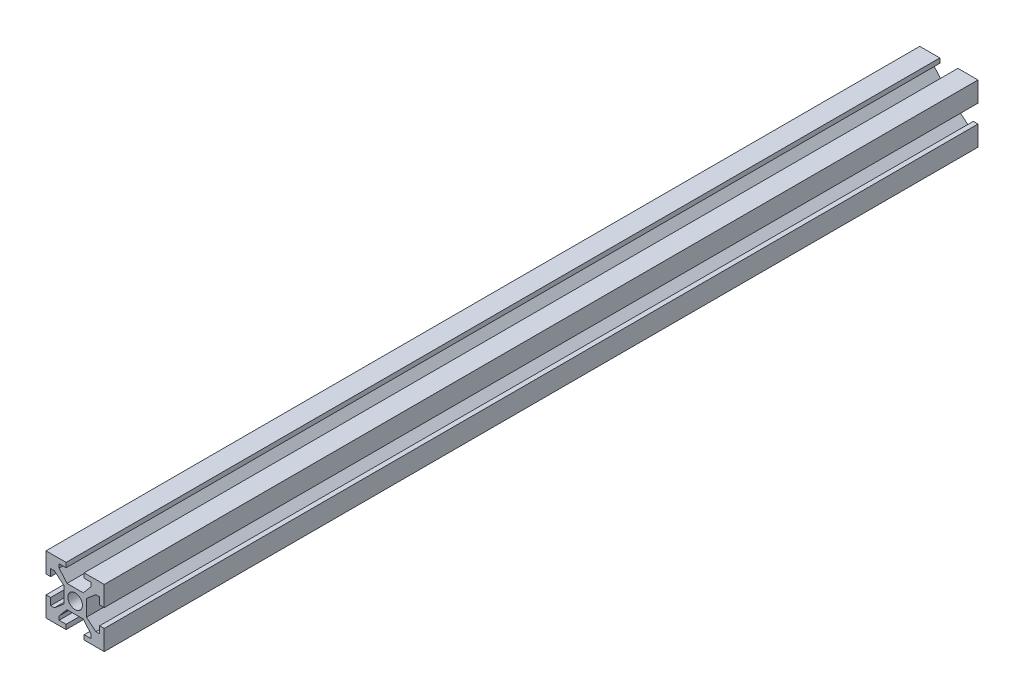
SolidWorks part; units mm, degrees
ref_plane "前视基准面" through (0, 0, 0) normal (0, 0, 1) x (1, 0, 0)
ref_plane "上视基准面" through (0, 0, 0) normal (0, 1, 0) x (1, 0, 0)
ref_plane "右视基准面" through (0, 0, 0) normal (1, 0, 0) x (0, 0, -1)
sketch "草图1" plane through (0, 0, 0) normal (0, 0, 1) x (1, 0, 0)
  line L0 (-10, 20) -> (-10, 0) construction
  line L1 (-20, 20) -> (-13.1, 20)
  line L2 (-20, 20) -> (-20, 13.1)
  line L3 (-20, 0) -> (-13.1, 0)
  line L4 (0, 20) -> (0, 13.1)
  line L5 (-20, 10) -> (0, 10) construction
  line L6 (-13.1, 20) -> (-13.1, 18.4)
  line L7 (-13.1, 18.4) -> (-15.5, 18.4)
  line L8 (-15.5, 18.4) -> (-15.5, 17.1043)
  line L9 (-15.5, 17.1043) -> (-12.797, 13.9)
  line L10 (-12.797, 13.9) -> (-7.203, 13.9)
  line L11 (-4.5, 17.1043) -> (-7.203, 13.9)
  line L12 (-4.5, 18.4) -> (-4.5, 17.1043)
  line L13 (-6.9, 20) -> (-6.9, 18.4)
  line L14 (-6.9, 18.4) -> (-4.5, 18.4)
  line L15 (-1.6, 13.1) -> (-1.6, 15.5)
  line L16 (-1.6, 15.5) -> (-2.8957, 15.5)
  line L17 (-2.8957, 15.5) -> (-6.1, 12.797)
  line L18 (-6.1, 12.797) -> (-6.1, 7.203)
  line L19 (-2.8957, 4.5) -> (-6.1, 7.203)
  line L20 (-1.6, 4.5) -> (-2.8957, 4.5)
  line L21 (-1.6, 6.9) -> (-1.6, 4.5)
  line L22 (0, 6.9) -> (-1.6, 6.9)
  line L23 (0, 13.1) -> (-1.6, 13.1)
  line L24 (-6.9, 1.6) -> (-4.5, 1.6)
  line L25 (-4.5, 1.6) -> (-4.5, 2.8957)
  line L26 (-4.5, 2.8957) -> (-7.203, 6.1)
  line L27 (-7.203, 6.1) -> (-12.797, 6.1)
  line L28 (-15.5, 2.8957) -> (-12.797, 6.1)
  line L29 (-15.5, 1.6) -> (-15.5, 2.8957)
  line L30 (-13.1, 1.6) -> (-15.5, 1.6)
  line L31 (-13.1, 0) -> (-13.1, 1.6)
  line L32 (-6.9, 0) -> (-6.9, 1.6)
  line L33 (-18.4, 6.9) -> (-18.4, 4.5)
  line L34 (-18.4, 4.5) -> (-17.1043, 4.5)
  line L35 (-17.1043, 4.5) -> (-13.9, 7.203)
  line L36 (-13.9, 7.203) -> (-13.9, 12.797)
  line L37 (-17.1043, 15.5) -> (-13.9, 12.797)
  line L38 (-18.4, 15.5) -> (-17.1043, 15.5)
  line L39 (-18.4, 13.1) -> (-18.4, 15.5)
  line L40 (-20, 13.1) -> (-18.4, 13.1)
  line L41 (-20, 6.9) -> (-18.4, 6.9)
  line L42 (-6.9, 20) -> (0, 20)
  line L43 (0, 6.9) -> (0, 0)
  line L44 (-20, 6.9) -> (-20, 0)
  line L45 (-6.9, 0) -> (0, 0)
  circle A0 centre (-10, 10) radius 2.5
  point P18 (-10, 13.9)
  point P55 (-10, 10)
  dimension "D3" = 5
  dimension "D1" = 20
  dimension "D2" = 20
  dimension "D4" = 5.5
  dimension "D5" = 6.1
  dimension "D6" = 3.1
  dimension "D7" = 1.6
  dimension "D8" = 4
extrude "凸台-拉伸1" add sketch "草图1" along normal blind 300
